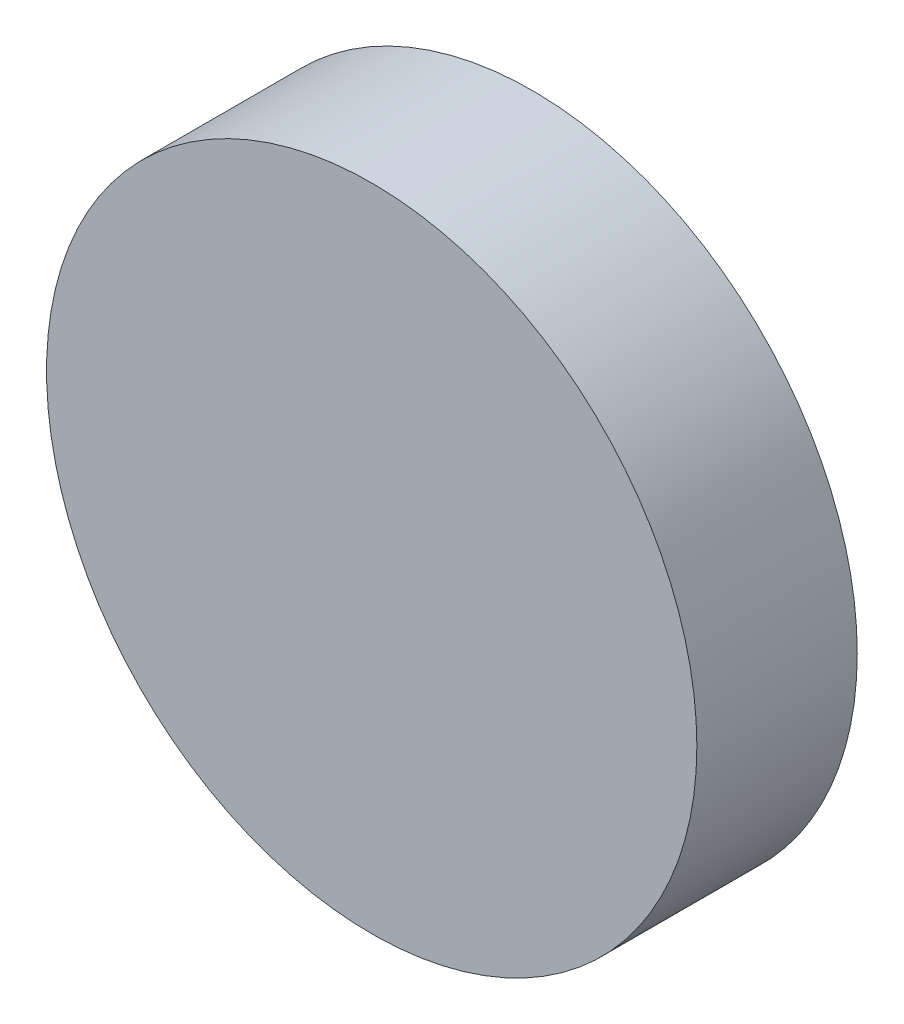
SolidWorks part; units mm, degrees
ref_plane "正面" through (0, 0, 0) normal (0, 0, 1) x (1, 0, 0)
ref_plane "平面" through (0, 0, 0) normal (0, 1, 0) x (1, 0, 0)
ref_plane "右側面" through (0, 0, 0) normal (1, 0, 0) x (0, 0, -1)
sketch "ｽｹｯﾁ1" plane through (0, 0, 0) normal (0, 0, 1) x (1, 0, 0)
  line L0 (0, 0) -> (0.2027, 0)
  line L1 (0, 0) -> (0.2027, 0.0016)
  line L2 (0, 0) -> (0.2027, -0.0035)
  circle A0 centre (0, 0) radius 0.2027
  dimension "D1" = 0.4054
  dimension "D2" = 0.463
  dimension "D3" = 0.983
extrude "ﾎﾞｽ - 押し出し1" add sketch "ｽｹｯﾁ1" along normal blind 0.1 contours A0
equation "\"r\" = 0.4054254316848883"
equation "\"fai0\" = 0.462529259279058"
equation "\"fai1\" = 0.9825062116788114"
equation "\"D1@ｽｹｯﾁ1\"=\"r\""
equation "\"D2@ｽｹｯﾁ1\"=\"fai0\""
equation "\"D3@ｽｹｯﾁ1\"=\"fai1\""
